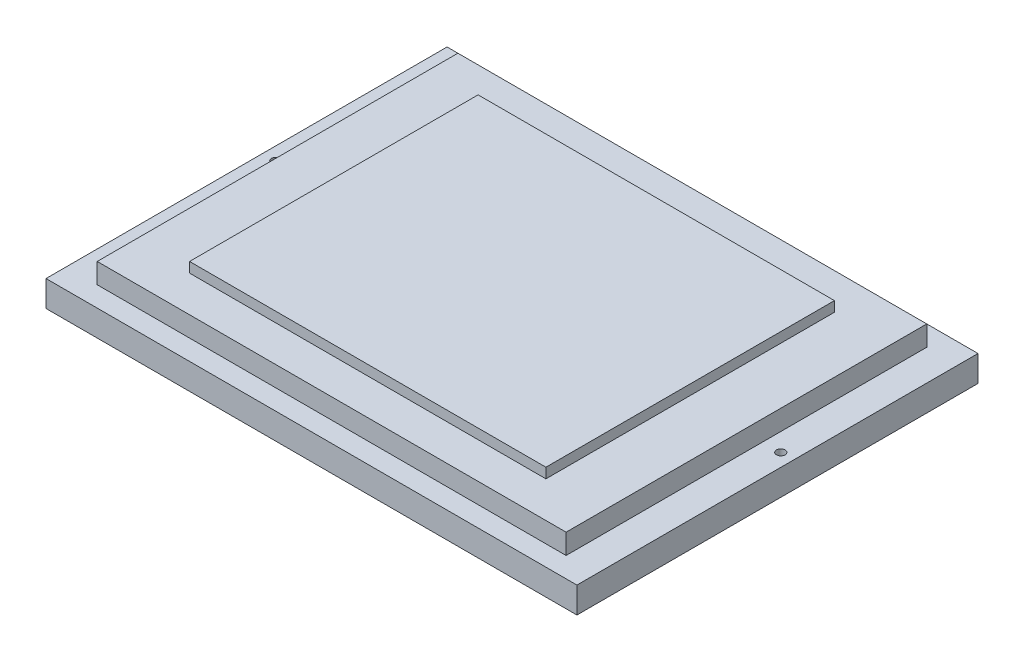
SolidWorks part; units mm, degrees
ref_plane "Front Plane" through (0, 0, 0) normal (0, 0, 1) x (1, 0, 0)
ref_plane "Top Plane" through (0, 0, 0) normal (0, 1, 0) x (1, 0, 0)
ref_plane "Right Plane" through (0, 0, 0) normal (1, 0, 0) x (0, 0, -1)
sketch "Sketch1" plane through (0, 0, 0) normal (0, 1, 0) x (1, 0, 0)
  line L1 (0, 0) -> (368, 0)
  line L2 (0, 0) -> (0, 278)
  line L3 (0, 278) -> (368, 278)
  line L4 (368, 0) -> (368, 278)
  dimension "D1" = 368
  dimension "D2" = 278
extrude "Boss-Extrude1" add sketch "Sketch1" against normal blind 39
sketch "Sketch2" plane through (0, 0, 0) normal (0, 1, 0) x (1, 0, 0)
  line L0 (368, 278) -> (0, 278) construction
  line L1 (21.5, 264) -> (346.5, 264)
  line L2 (21.5, 264) -> (21.5, 14)
  line L3 (21.5, 14) -> (346.5, 14)
  line L4 (346.5, 264) -> (346.5, 14)
  line L5 (368, 0) -> (368, 278) construction
  line L8 (0, 278) -> (368, 278)
  line L9 (0, 278) -> (0, 0)
  line L10 (0, 0) -> (368, 0)
  line L11 (368, 278) -> (368, 0)
  point P6 (184, 278)
  point P7 (184, 264)
  point P8 (346.5, 139)
  point P11 (368, 139)
  dimension "D1" = 325
  dimension "D2" = 250
extrude "Cut-Extrude1" cut sketch "Sketch2" against normal blind 21
sketch "Sketch3" plane through (0, 0, 0) normal (0, 1, 0) x (1, 0, 0)
  line L1 (21.5, 264) -> (346.5, 264)
  line L2 (21.5, 264) -> (21.5, 14)
  line L3 (21.5, 14) -> (346.5, 14)
  line L4 (346.5, 264) -> (346.5, 14)
  line L5 (60.5, 239) -> (307.5, 239)
  line L6 (60.5, 239) -> (60.5, 39)
  line L7 (60.5, 39) -> (307.5, 39)
  line L8 (307.5, 239) -> (307.5, 39)
  point P10 (184, 239)
  point P11 (184, 264)
  point P12 (346.5, 139)
  point P13 (307.5, 139)
  dimension "D1" = 247
  dimension "D2" = 200
extrude "Cut-Extrude2" cut sketch "Sketch3" against normal blind 7
sketch "Sketch4" plane through (0, 0, 0) normal (0, 1, 0) x (1, 0, 0)
  line L0 (0, 278) -> (0, 0) construction
  line L2 (368, 0) -> (368, 278) construction
  circle A0 centre (9, 150.3) radius 3
  circle A1 centre (359, 150.3) radius 3
  point P6 (0, 139)
  point P9 (368, 139)
  dimension "D1" = 6
  dimension "D2" = 6
  dimension "D3" = 11.3
  dimension "D4" = 11.3
  dimension "D5" = 9
  dimension "D6" = 9
extrude "Cut-Extrude3" cut sketch "Sketch4" against normal blind 59
